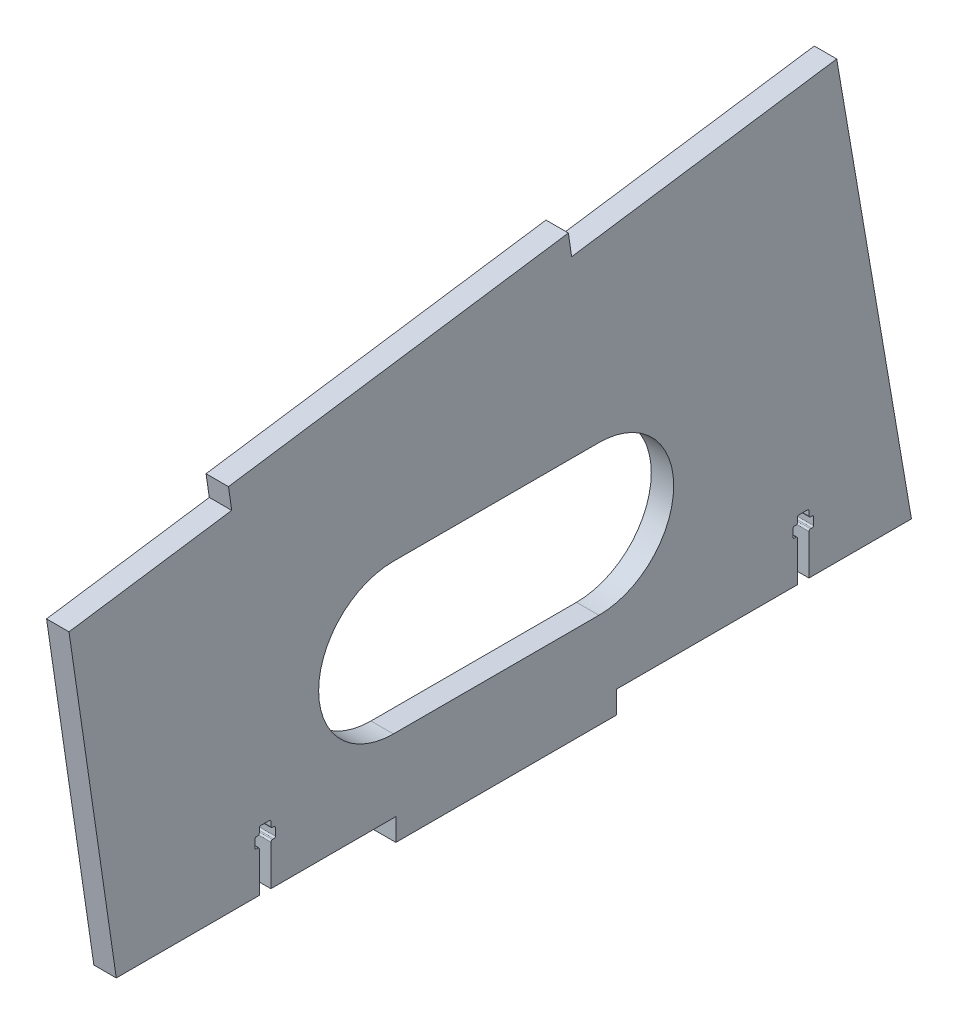
SolidWorks part; units mm, degrees
ref_plane "Front Plane" through (0, 0, 0) normal (0, 0, 1) x (1, 0, 0)
ref_plane "Top Plane" through (0, 0, 0) normal (0, 1, 0) x (1, 0, 0)
ref_plane "Right Plane" through (0, 0, 0) normal (1, 0, 0) x (0, 0, -1)
sketch "Sketch1" plane through (0, 0, 0) normal (1, 0, 0) x (0, 0, -1)
  line L0 (-8.4239, 100.4207) -> (5.8464, 2.8074)
  line L5 (5.8464, 2.8074) -> (224.8136, 2.8074)
  line L6 (224.8136, 2.8074) -> (203.793, 125.3814)
  line L7 (203.793, 125.3814) -> (199.8548, 130.8695)
  line L8 (199.8548, 130.8695) -> (-8.4239, 100.4207)
extrude "Boss-Extrude1" add sketch "Sketch1" along normal blind 6
sketch "Sketch2" plane through (6, 0, 0) normal (1, 0, 0) x (0, 0, -1)
  line L0 (5.8464, 2.8074) -> (85.8464, 2.8074)
  line L1 (5.8464, 2.8074) -> (224.8136, 2.8074) construction
  line L2 (85.8464, 2.8074) -> (85.8464, 8.8074)
  line L3 (85.8464, 8.8074) -> (4.9693, 8.8074)
  line L4 (-8.4239, 100.4207) -> (5.8464, 2.8074) construction
  line L5 (4.9693, 8.8074) -> (5.8464, 2.8074)
  line L6 (144.8136, 2.8074) -> (144.8136, 8.8074)
  line L7 (144.8136, 8.8074) -> (223.7847, 8.8074)
  line L8 (224.8136, 2.8074) -> (203.793, 125.3814) construction
  line L9 (223.7847, 8.8074) -> (224.8136, 2.8074)
  line L10 (224.8136, 2.8074) -> (144.8136, 2.8074)
  line L11 (41.0502, 107.6535) -> (41.9182, 101.7166)
  line L12 (199.8548, 130.8695) -> (-8.4239, 100.4207) construction
  line L13 (41.9182, 101.7166) -> (-7.556, 94.4838)
  line L14 (-7.556, 94.4838) -> (-8.4239, 100.4207)
  line L15 (-8.4239, 100.4207) -> (41.0502, 107.6535)
  line L16 (131.9993, 120.9495) -> (132.8672, 115.0126)
  line L17 (132.8672, 115.0126) -> (203.793, 125.3814)
  line L18 (199.8548, 130.8695) -> (203.793, 125.3814)
  line L19 (199.8548, 130.8695) -> (131.9993, 120.9495)
  dimension "D1" = 80
  dimension "D2" = 6
  dimension "D3" = 80
  dimension "D4" = 6
  dimension "D5" = 6
  dimension "D6" = 50
  dimension "D7" = 6
  dimension "D8" = 91.9158
  dimension "D9" = 58.9672
extrude "Cut-Extrude1" cut sketch "Sketch2" against normal blind 6
sketch "Sketch4" plane through (6, 0, 0) normal (1, 0, 0) x (0, 0, -1)
  line L0 (-7.556, 94.4838) -> (-1.6191, 95.3518)
  line L1 (-7.556, 94.4838) -> (41.9182, 101.7166) construction
  line L2 (-1.6191, 95.3518) -> (11.033, 8.8074)
  line L3 (85.8464, 8.8074) -> (4.9693, 8.8074) construction
  line L4 (11.033, 8.8074) -> (4.9693, 8.8074)
  line L5 (4.9693, 8.8074) -> (-7.556, 94.4838)
  dimension "D1" = 6
extrude "Cut-Extrude2" cut sketch "Sketch4" against normal blind 6
sketch "Sketch5" plane through (6, 0, 0) normal (1, 0, 0) x (0, 0, -1)
  line L0 (85.8464, 8.8074) -> (11.033, 8.8074) construction
  line L1 (49.2964, 8.8074) -> (52.3964, 8.8074)
  line L2 (49.2964, 8.8074) -> (49.2964, 24.8074)
  line L3 (49.2964, 24.8074) -> (52.3964, 24.8074)
  line L4 (52.3964, 8.8074) -> (52.3964, 24.8074)
  line L5 (223.7847, 8.8074) -> (144.8136, 8.8074) construction
  line L6 (193.2636, 8.8074) -> (196.3636, 8.8074)
  line L7 (193.2636, 8.8074) -> (193.2636, 24.8074)
  line L8 (193.2636, 24.8074) -> (196.3636, 24.8074)
  line L9 (196.3636, 8.8074) -> (196.3636, 24.8074)
  line L10 (85.8464, 2.8074) -> (85.8464, 8.8074) construction
  line L11 (144.8136, 8.8074) -> (144.8136, 2.8074) construction
  point P14 (50.8464, 8.8074)
  point P15 (194.8136, 8.8074)
  dimension "D1" = 3.1
  dimension "D2" = 3.1
  dimension "D3" = 16
  dimension "D4" = 16
  dimension "D5" = 35
  dimension "D6" = 50
extrude "Cut-Extrude3" cut sketch "Sketch5" against normal through all
sketch "Sketch6" plane through (6, 0, 0) normal (1, 0, 0) x (0, 0, -1)
  line L0 (196.3636, 24.8074) -> (193.2636, 24.8074) construction
  line L1 (48.0964, 22.8074) -> (53.5964, 22.8074)
  line L2 (48.0964, 22.8074) -> (48.0964, 20.0074)
  line L3 (48.0964, 20.0074) -> (53.5964, 20.0074)
  line L4 (53.5964, 22.8074) -> (53.5964, 20.0074)
  line L5 (192.0636, 22.8074) -> (197.5636, 22.8074)
  line L6 (192.0636, 22.8074) -> (192.0636, 20.0074)
  line L7 (192.0636, 20.0074) -> (197.5636, 20.0074)
  line L8 (197.5636, 22.8074) -> (197.5636, 20.0074)
  line L9 (193.2636, 24.8074) -> (193.2636, 8.8074) construction
  line L10 (52.3964, 24.8074) -> (49.2964, 24.8074) construction
  line L11 (49.2964, 24.8074) -> (49.2964, 8.8074) construction
  dimension "D1" = 5.5
  dimension "D2" = 2.8
  dimension "D3" = 5.5
  dimension "D4" = 2.8
  dimension "D5" = 2
  dimension "D6" = 1.2
  dimension "D7" = 2
  dimension "D8" = 1.2
extrude "Cut-Extrude4" cut sketch "Sketch6" against normal through all
fillet "Fillet1" radius 0.4 20 edges at (3, 20.0074, -196.3636) (3, 20.0074, -197.5636) (3, 22.8074, -197.5636) (3, 22.8074, -196.3636) (3, 24.8074, -196.3636) (3, 24.8074, -193.2636) (3, 22.8074, -193.2636) (3, 22.8074, -192.0636) (3, 20.0074, -192.0636) (3, 20.0074, -193.2636) (3, 20.0074, -52.3964) (3, 20.0074, -53.5964) (3, 22.8074, -53.5964) (3, 22.8074, -52.3964) (3, 24.8074, -52.3964) (3, 24.8074, -49.2964) (3, 22.8074, -49.2964) (3, 22.8074, -48.0964) (3, 20.0074, -48.0964) (3, 20.0074, -49.2964)
sketch "Sketch7" plane through (6, 0, 0) normal (1, 0, 0) x (0, 0, -1)
  line L0 (85.1732, 48.2902) -> (140.1732, 48.2902) construction
  line L1 (85.1732, 68.2902) -> (140.1732, 68.2902)
  line L2 (85.1732, 28.2902) -> (140.1732, 28.2902)
  arc A0 (85.1732, 68.2902) -> (85.1732, 28.2902) centre (85.1732, 48.2902) ccw
  arc A1 (140.1732, 28.2902) -> (140.1732, 68.2902) centre (140.1732, 48.2902) ccw
  point P2 (112.6732, 48.2902)
  dimension "D1" = 55
  dimension "D2" = 40
extrude "Cut-Extrude5" cut sketch "Sketch7" against normal through all
